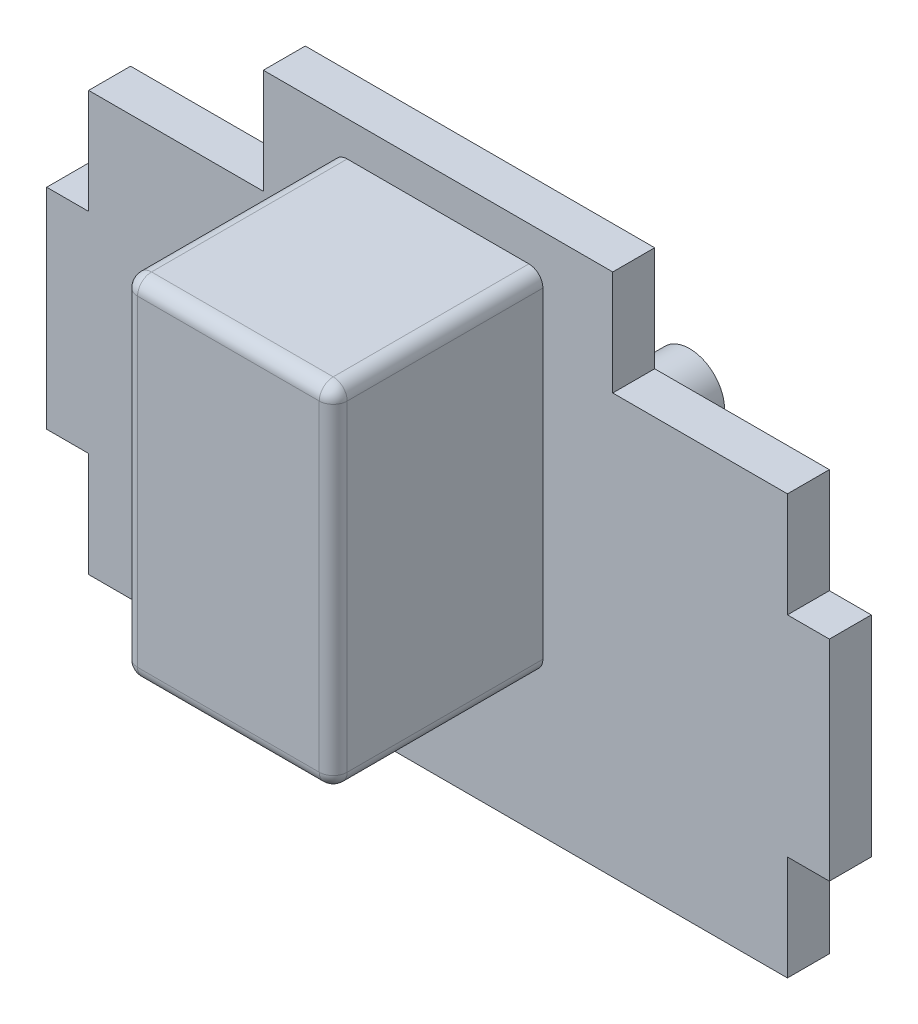
SolidWorks part; units mm, degrees
ref_plane "Front Plane" through (0, 0, 0) normal (0, 0, 1) x (1, 0, 0)
ref_plane "Top Plane" through (0, 0, 0) normal (0, 1, 0) x (1, 0, 0)
ref_plane "Right Plane" through (0, 0, 0) normal (1, 0, 0) x (0, 0, -1)
sketch "Sketch2" plane through (0, 0, 0) normal (0, 0, 1) x (1, 0, 0)
  line L0 (-1.25, 0) -> (1.25, 0)
  line L1 (1.25, 0) -> (1.25, -1.25)
  line L2 (1.25, -1.25) -> (2.5, -1.25)
  line L3 (2.5, -1.25) -> (2.5, -2)
  line L4 (2.5, -2) -> (2.8, -2)
  line L5 (2.8, -2) -> (2.8, -3.5)
  line L6 (2.8, -3.5) -> (2.5, -3.5)
  line L7 (2.5, -3.5) -> (2.5, -4.25)
  line L8 (2.5, -4.25) -> (-2.5, -4.25)
  line L9 (0, 0) -> (0, -4.25) construction
  line L10 (-2.5, -3.5) -> (-2.5, -4.25)
  line L11 (-2.8, -3.5) -> (-2.5, -3.5)
  line L12 (-2.8, -2) -> (-2.8, -3.5)
  line L13 (-2.5, -2) -> (-2.8, -2)
  line L14 (-2.5, -1.25) -> (-2.5, -2)
  line L15 (-1.25, -1.25) -> (-2.5, -1.25)
  line L16 (-1.25, 0) -> (-1.25, -1.25)
  dimension "D1" = 1.25
  dimension "D2" = 1.25
  dimension "D3" = 1.25
  dimension "D4" = 0.75
  dimension "D5" = 1.5
  dimension "D6" = 0.3
  dimension "D7" = 0.3
  dimension "D8" = 0.75
extrude "Boss-Extrude1" add sketch "Sketch2" along normal blind 0.3
sketch "Sketch3" plane through (0, 0, 0.3) normal (0, 0, 1) x (1, 0, 0)
  line L0 (0, 0) -> (0, -4.25) construction
  line L1 (-2.5, -4.25) -> (2.5, -4.25) construction
  line L2 (0, 0) -> (-0.75, 0) construction
  line L3 (1.25, 0) -> (-1.25, 0) construction
  line L4 (0, 0) -> (0.75, 0) construction
  line L5 (0, 10) -> (-0.75, 10)
  line L6 (0, -0.75) -> (0.75, -0.75)
  line L7 (0, -0.75) -> (-0.75, -0.75)
  line L8 (-0.75, -0.75) -> (-0.75, -3.25)
  line L9 (-0.75, -3.25) -> (0.75, -3.25)
  line L10 (0.75, -3.25) -> (0.75, -0.75)
  dimension "D1" = 0.75
  dimension "D2" = 0.75
  dimension "D5" = 2.5
  dimension "D3" = 10
  dimension "D4" = 0.75
extrude "Boss-Extrude2" add sketch "Sketch3" along normal blind 1.5 contours L9 L10 L6 L7 L8
fillet "Fillet1" radius 0.1 8 edges at (-0.75, -0.75, 1.05) (-0.75, -2, 1.8) (-0.75, -3.25, 1.05) (0, -3.25, 1.8) (0.75, -3.25, 1.05) (0, -0.75, 1.8) (0.75, -2, 1.8) (0.75, -0.75, 1.05)
sketch "Sketch4" plane through (0, 0, 0) normal (0, 0, -1) x (-1, 0, 0)
  line L0 (0, -4.25) -> (0, -2.75) construction
  line L1 (2.5, -4.25) -> (-2.5, -4.25) construction
  circle A0 centre (0, -2.75) radius 0.25
  dimension "D2" = 0.5
  dimension "D1" = 1.5
extrude "Boss-Extrude3" add sketch "Sketch4" along normal blind 1.5
sketch "Sketch5" plane through (0, 0, 0) normal (0, 0, -1) x (-1, 0, 0)
  line L0 (-1.25, 0) -> (-1.25, -0.5)
  line L1 (-1.25, -1.25) -> (-1.25, 0) construction
  line L2 (-1.25, -0.5) -> (1.25, -0.5)
  line L3 (1.25, 0) -> (1.25, -1.25) construction
  line L4 (1.25, -0.5) -> (1.25, 0)
  line L5 (1.25, 0) -> (-1.25, 0)
  dimension "D1" = 0.5
extrude "Cut-Extrude1" cut sketch "Sketch5" against normal blind 10
